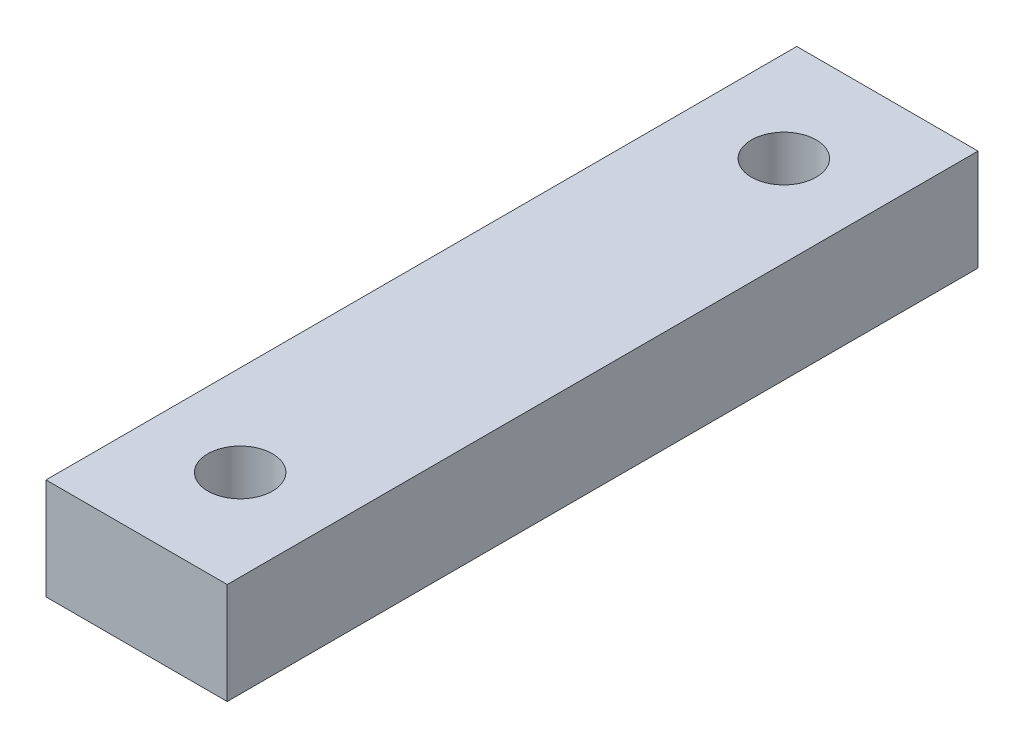
SolidWorks part; units mm, degrees
ref_plane "Front Plane" through (0, 0, 0) normal (0, 0, 1) x (1, 0, 0)
ref_plane "Top Plane" through (0, 0, 0) normal (0, 1, 0) x (1, 0, 0)
ref_plane "Right Plane" through (0, 0, 0) normal (1, 0, 0) x (0, 0, -1)
sketch "Sketch1" plane through (0, 0, 0) normal (0, 1, 0) x (1, 0, 0)
  line L0 (7, 58) -> (7, 0) construction
  line L1 (0, 0) -> (14, 0)
  line L2 (0, 0) -> (0, 58)
  line L3 (0, 58) -> (14, 58)
  line L4 (14, 0) -> (14, 58)
  line L5 (0, 29) -> (14, 29) construction
  circle A0 centre (7, 50) radius 2.5
  circle A1 centre (7, 8) radius 2.5
  dimension "D4" = 5
  dimension "D1" = 58
  dimension "D2" = 14
  dimension "D3" = 42
extrude "Boss-Extrude1" add sketch "Sketch1" along normal blind 7.83 contours L1 L4 L3 L2 A0 A1
